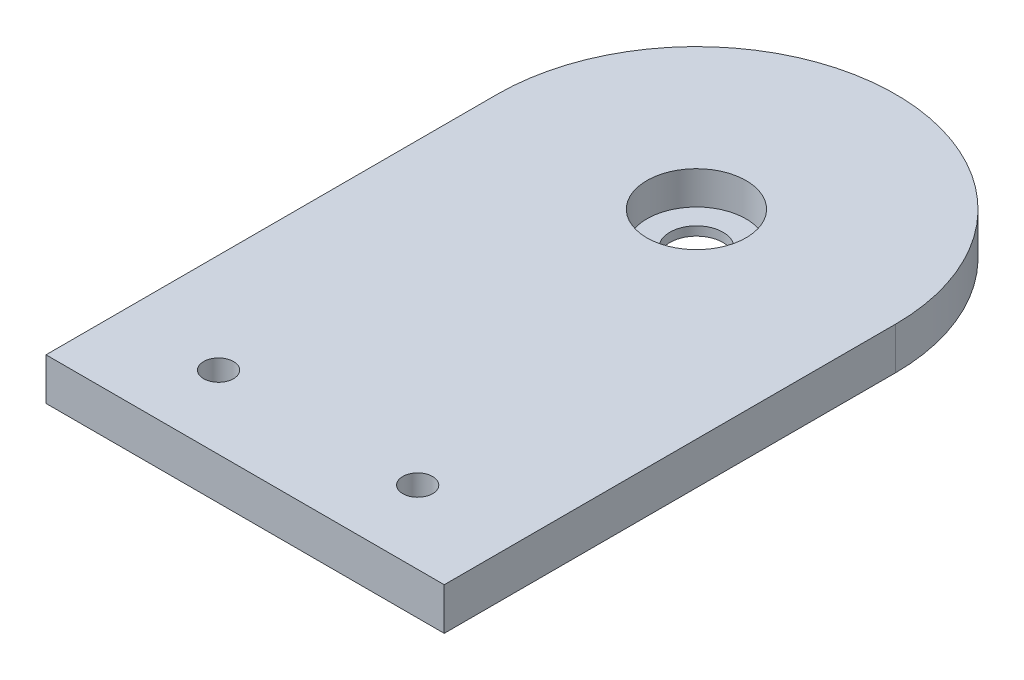
SolidWorks part; units mm, degrees
material "Aleación 6061"
ref_plane "Alzado" through (0, 0, 0) normal (0, 0, 1) x (1, 0, 0)
ref_plane "Planta" through (0, 0, 0) normal (0, 1, 0) x (1, 0, 0)
ref_plane "Vista lateral" through (0, 0, 0) normal (1, 0, 0) x (0, 0, -1)
sketch "Sk_Placa" plane through (0, 0, 0) normal (0, 1, 0) x (1, 0, 0)
  line L1 (-30, -379) -> (30, -379)
  line L2 (-30, -379) -> (-30, -330)
  line L3 (-30, -330) -> (30, -330)
  line L4 (30, -379) -> (30, -330)
  line L5 (-30, -379) -> (30, -330) construction
  line L6 (-30, -330) -> (30, -379) construction
  point P0 (0, -354.5)
  dimension "D1" = 60
  dimension "D2" = 49
  dimension "D3" = 354.5
extrude "Placa" add sketch "Sk_Placa" along normal blind 6.35 from offset 66.1
sketch "Sk_Extremo" plane through (0, 0, 0) normal (0, 1, 0) x (1, 0, 0)
  circle A0 centre (0, -330) radius 30
  dimension "D1" = 60
  dimension "D2" = 330
extrude "Extremo" add sketch "Sk_Extremo" along normal blind 6.35 from offset 66.1
sketch "Sk_Alojamiento_696ZZ" plane through (0, 0, 0) normal (0, 1, 0) x (1, 0, 0)
  circle A0 centre (0, -330) radius 7.475
  dimension "D1" = 14.95
  dimension "D2" = 330
extrude "Alojamiento_696ZZ" cut sketch "Sk_Alojamiento_696ZZ" along normal blind 5 from offset 64.75
sketch "Sk_Paso_extractor" plane through (0, 0, 0) normal (0, 1, 0) x (1, 0, 0)
  circle A0 centre (0, -330) radius 4
  dimension "D1" = 8
  dimension "D2" = 330
extrude "Paso_extractor" cut sketch "Sk_Paso_extractor" along normal blind 1.35 from offset 66.1
sketch "Sk_Extension_pestanas" plane through (0, 0, 0) normal (0, 1, 0) x (1, 0, 0)
  line L1 (-30, -398) -> (30, -398)
  line L2 (-30, -398) -> (-30, -379)
  line L3 (-30, -379) -> (30, -379)
  line L4 (30, -398) -> (30, -379)
  line L5 (-30, -398) -> (30, -379) construction
  line L6 (-30, -379) -> (30, -398) construction
  point P0 (0, -388.5)
  dimension "D1" = 60
  dimension "D2" = 19
  dimension "D3" = 388.5
extrude "Extension_pestanas" add sketch "Sk_Extension_pestanas" along normal blind 6.35 from offset 66.1
sketch "Sk_Pasantes_M4_repisa" plane through (0, 0, 0) normal (0, 1, 0) x (1, 0, 0)
  circle A0 centre (-15, -387) radius 2.25
  circle A1 centre (15, -387) radius 2.25
  dimension "D1" = 4.5
  dimension "D4" = 4.5
  dimension "D2" = 15
  dimension "D3" = 387
  dimension "D5" = 15
  dimension "D6" = 387
extrude "Pasantes_M4_repisa" cut sketch "Sk_Pasantes_M4_repisa" along normal blind 6.35 from offset 66.1
